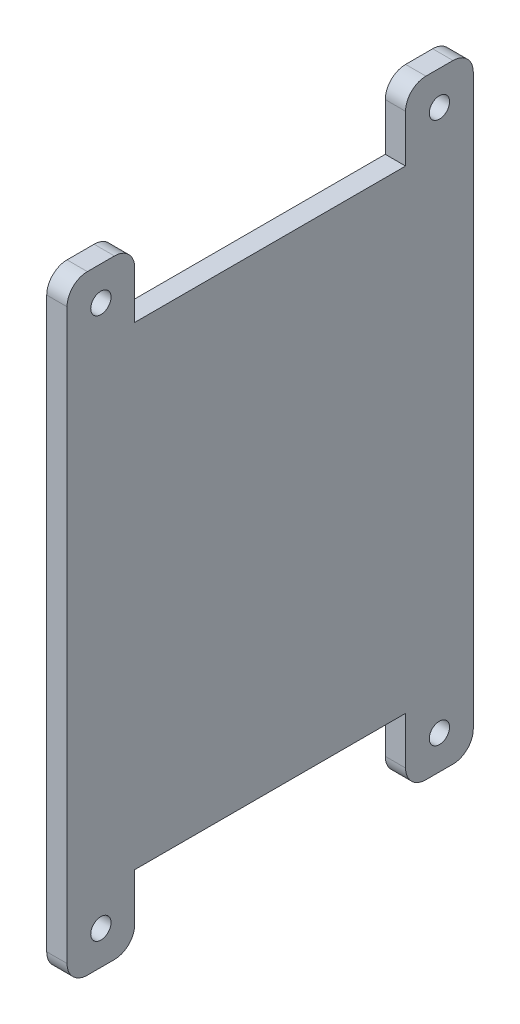
SolidWorks part; units mm, degrees
material "Cobre"
ref_plane "Plano frontal" through (0, 0, 0) normal (0, 0, 1) x (1, 0, 0)
ref_plane "Plano superior" through (0, 0, 0) normal (0, 1, 0) x (1, 0, 0)
ref_plane "Plano direito" through (0, 0, 0) normal (1, 0, 0) x (0, 0, -1)
sketch "Esboço3" plane through (0, 0, 0) normal (1, 0, 0) x (0, 0, -1)
  line L1 (-1.8635, 22.6001) -> (38.1365, 22.6001)
  line L2 (-11.8635, 22.6001) -> (-11.8635, -47.3999)
  line L3 (-1.8635, -47.3999) -> (38.1365, -47.3999)
  line L4 (48.1365, 22.6001) -> (48.1365, -47.3999)
  line L6 (-11.8635, 22.6001) -> (-11.8635, 29.6001)
  line L7 (-8.8635, 32.6001) -> (-4.8635, 32.6001)
  line L8 (-1.8635, 22.6001) -> (-1.8635, 29.6001)
  line L10 (48.1365, 22.6001) -> (48.1365, 29.6001)
  line L11 (45.1365, 32.6001) -> (41.1365, 32.6001)
  line L12 (38.1365, 22.6001) -> (38.1365, 29.6001)
  line L14 (-11.8635, -47.3999) -> (-11.8635, -54.3999)
  line L15 (-8.8635, -57.3999) -> (-4.8635, -57.3999)
  line L16 (-1.8635, -47.3999) -> (-1.8635, -54.3999)
  line L18 (48.1365, -47.3999) -> (48.1365, -54.3999)
  line L19 (45.1365, -57.3999) -> (41.1365, -57.3999)
  line L20 (38.1365, -47.3999) -> (38.1365, -54.3999)
  arc A0 (-11.8635, 29.6001) -> (-8.8635, 32.6001) centre (-8.8635, 29.6001) cw
  arc A1 (-4.8635, 32.6001) -> (-1.8635, 29.6001) centre (-4.8635, 29.6001) cw
  arc A2 (41.1365, 32.6001) -> (38.1365, 29.6001) centre (41.1365, 29.6001) ccw
  arc A3 (48.1365, 29.6001) -> (45.1365, 32.6001) centre (45.1365, 29.6001) ccw
  arc A4 (48.1365, -54.3999) -> (45.1365, -57.3999) centre (45.1365, -54.3999) cw
  arc A5 (41.1365, -57.3999) -> (38.1365, -54.3999) centre (41.1365, -54.3999) cw
  arc A6 (-4.8635, -57.3999) -> (-1.8635, -54.3999) centre (-4.8635, -54.3999) ccw
  arc A7 (-11.8635, -54.3999) -> (-8.8635, -57.3999) centre (-8.8635, -54.3999) ccw
  point P18 (-11.8635, 32.6001)
  point P21 (-1.8635, 32.6001)
  point P24 (38.1365, 32.6001)
  point P27 (48.1365, 32.6001)
  point P30 (48.1365, -57.3999)
  point P33 (38.1365, -57.3999)
  point P36 (-1.8635, -57.3999)
  point P39 (-11.8635, -57.3999)
  dimension "D11" = 3
  dimension "D1" = 70
  dimension "D2" = 60
  dimension "D3" = 10
  dimension "D4" = 10
  dimension "D5" = 10
  dimension "D6" = 10
  dimension "D7" = 10
  dimension "D8" = 10
  dimension "D9" = 10
  dimension "D10" = 10
extrude "PCB" add sketch "Esboço3" along normal blind 3
sketch "Esboço4" plane through (0, 0, 0) normal (-1, 0, 0) x (0, 0, 1)
  line L0 (-38.1365, 29.6001) -> (-38.1365, 22.6001) construction
  line L1 (-45.1365, 32.6001) -> (-41.1365, 32.6001) construction
  line L2 (11.8635, 29.6001) -> (11.8635, -54.3999) construction
  line L3 (4.8635, 32.6001) -> (8.8635, 32.6001) construction
  line L4 (-38.1365, -47.3999) -> (-38.1365, -54.3999) construction
  line L5 (-41.1365, -57.3999) -> (-45.1365, -57.3999) construction
  line L6 (8.8635, -57.3999) -> (4.8635, -57.3999) construction
  circle A0 centre (-43.1365, 27.6001) radius 1.5
  circle A1 centre (6.8635, 27.6001) radius 1.5
  circle A2 centre (6.8635, -52.3999) radius 1.5
  circle A3 centre (-43.1365, -52.3999) radius 1.5
  point P10 (-38.1365, 26.1001)
  point P17 (6.8635, 32.6001)
  dimension "D1" = 5
  dimension "D2" = 5
  dimension "D3" = 5
  dimension "D4" = 5
  dimension "D5" = 5
  dimension "D6" = 5
  dimension "D7" = 5
  dimension "D8" = 5
  dimension "D9" = 3
  dimension "D10" = 3
  dimension "D11" = 3
  dimension "D12" = 3
extrude "Furos PCB" cut sketch "Esboço4" against normal through all
